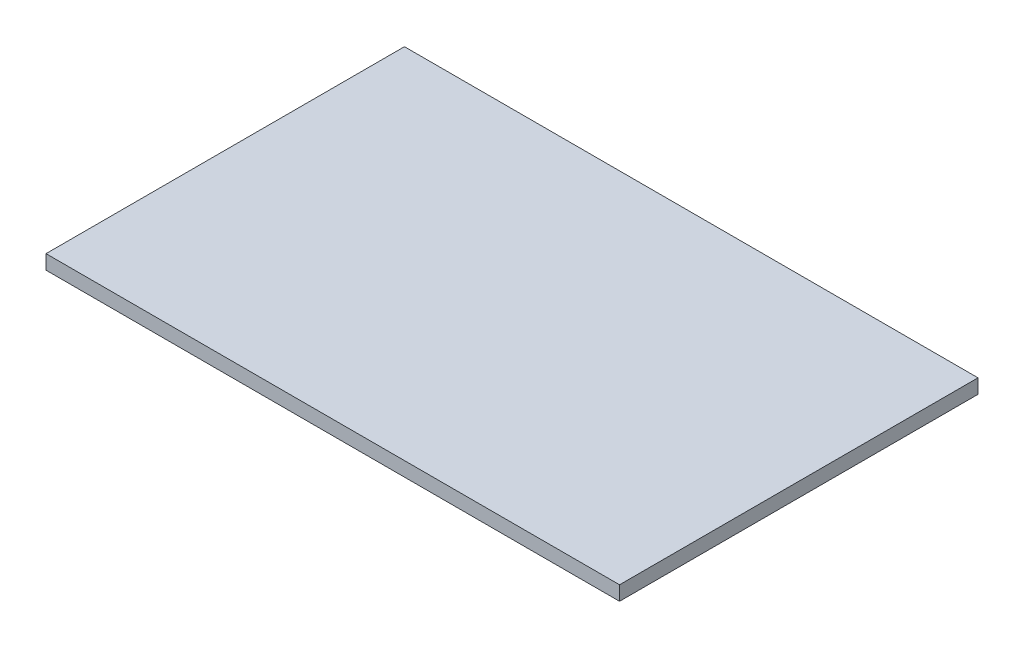
SolidWorks part; units mm, degrees
material "1023 Carbon Steel Sheet (SS)"
ref_plane "Front Plane" through (0, 0, 0) normal (0, 0, 1) x (1, 0, 0)
ref_plane "Top Plane" through (0, 0, 0) normal (0, 1, 0) x (1, 0, 0)
ref_plane "Right Plane" through (0, 0, 0) normal (1, 0, 0) x (0, 0, -1)
sketch "Sketch1" plane through (0, 0, 0) normal (0, 1, 0) x (1, 0, 0)
  line L1 (0, 0) -> (120, 0)
  line L2 (0, 0) -> (0, 75)
  line L3 (0, 75) -> (120, 75)
  line L4 (120, 0) -> (120, 75)
  dimension "D1" = 120
  dimension "D2" = 75
extrude "Boss-Extrude1" add sketch "Sketch1" along normal blind 3
